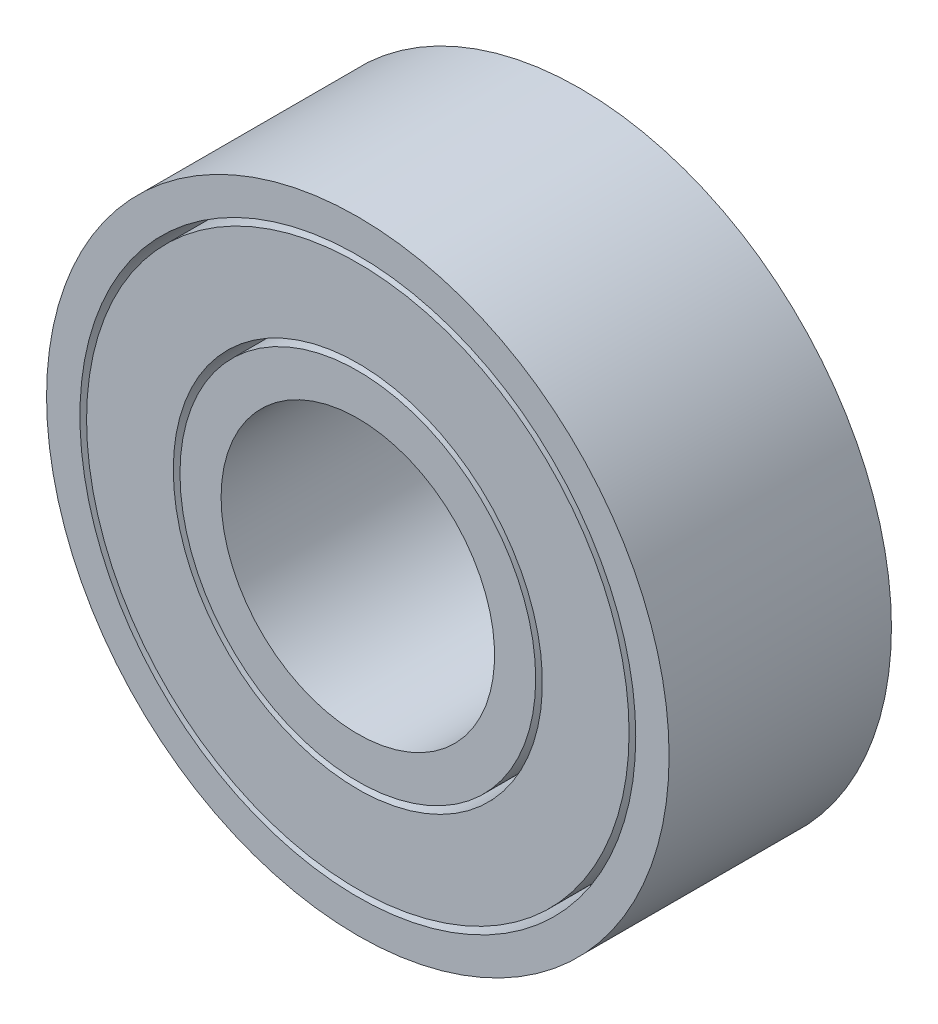
SolidWorks part; units mm, degrees
ref_plane "Front Plane" through (0, 0, 0) normal (0, 0, 1) x (1, 0, 0)
ref_plane "Top Plane" through (0, 0, 0) normal (0, 1, 0) x (1, 0, 0)
ref_plane "Right Plane" through (0, 0, 0) normal (1, 0, 0) x (0, 0, -1)
sketch "Sketch1" plane through (0, 0, 0) normal (0, 0, 1) x (1, 0, 0)
  circle A0 centre (0, 0) radius 14
  circle A1 centre (0, 0) radius 12.5
  dimension "D1" = 28
  dimension "D2" = 25
extrude "Boss-Extrude1" add sketch "Sketch1" along normal blind 10
sketch "Sketch2" plane through (0, 0, 0) normal (0, 0, -1) x (-1, 0, 0)
  circle A0 centre (0, 0) radius 12.2
  circle A1 centre (0, 0) radius 8.3
  dimension "D1" = 16.6
extrude "Boss-Extrude2" add sketch "Sketch2" against normal blind 10 separate body
sketch "Sketch3" plane through (0, 0, 0) normal (0, 0, -1) x (-1, 0, 0)
  circle A0 centre (0, 0) radius 8
  circle A1 centre (0, 0) radius 6.15
extrude "Boss-Extrude3" add sketch "Sketch3" against normal blind 10 separate body
